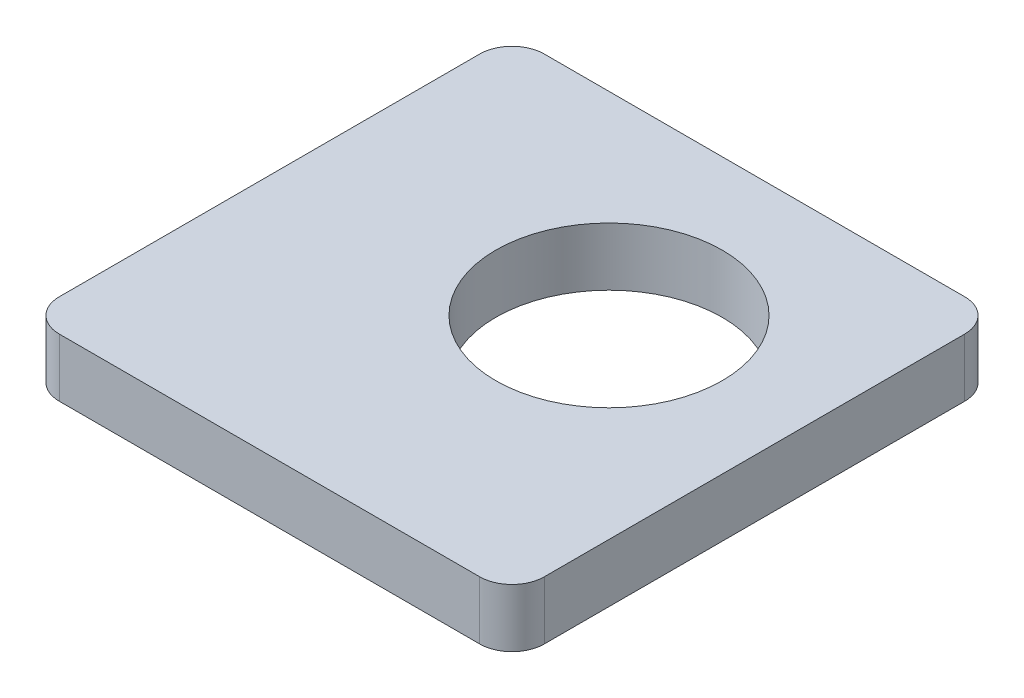
SolidWorks part; units mm, degrees
ref_plane "前视基准面" through (0, 0, 0) normal (0, 0, 1) x (1, 0, 0)
ref_plane "上视基准面" through (0, 0, 0) normal (0, 1, 0) x (1, 0, 0)
ref_plane "右视基准面" through (0, 0, 0) normal (1, 0, 0) x (0, 0, -1)
other "Configuration Table"
sketch "草图1" plane through (0, 0, 0) normal (0, 1, 0) x (1, 0, 0)
  line L1 (-75, -75) -> (75, -75)
  line L2 (-75, -75) -> (-75, 75)
  line L3 (-75, 75) -> (75, 75)
  line L4 (75, -75) -> (75, 75)
  circle A0 centre (15, 15) radius 35
  point P4 (-75, 0)
  point P6 (0, 75)
  dimension "D3" = 70
  dimension "D4" = 60
  dimension "D5" = 60
  dimension "D1" = 150
  dimension "D2" = 150
extrude "凸台-拉伸1" add sketch "草图1" along normal blind 18
fillet "圆角1" radius 10 4 edges at (-75, 9, -75) (75, 9, -75) (75, 9, 75) (-75, 9, 75)
